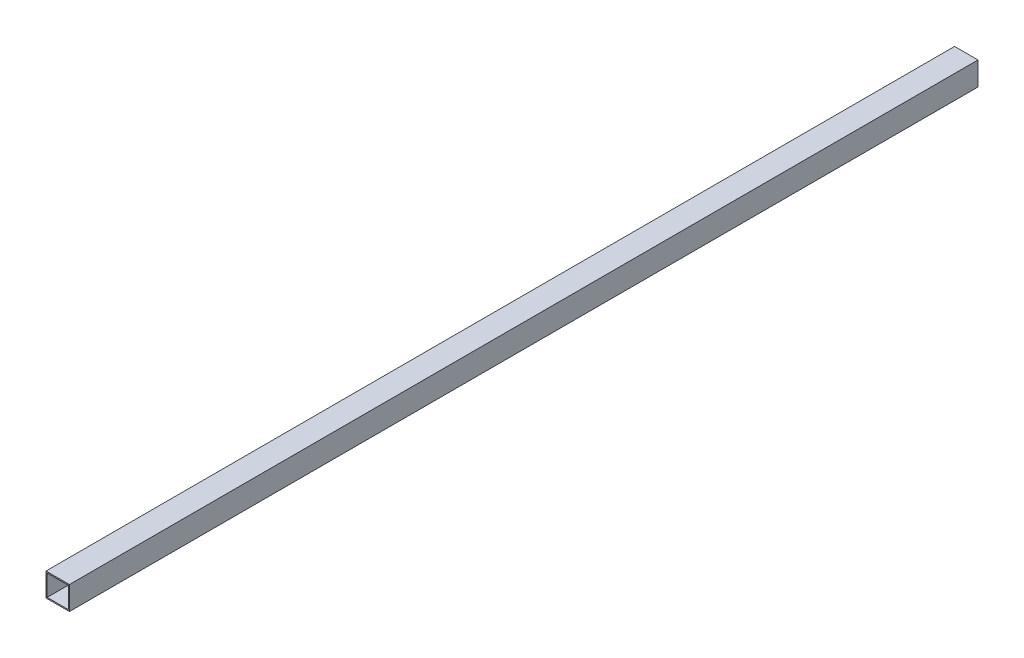
SolidWorks part; units mm, degrees
ref_plane "Front Plane" through (0, 0, 0) normal (0, 0, 1) x (1, 0, 0)
ref_plane "Top Plane" through (0, 0, 0) normal (0, 1, 0) x (1, 0, 0)
ref_plane "Right Plane" through (0, 0, 0) normal (1, 0, 0) x (0, 0, -1)
sketch "Sketch1" plane through (0, 0, 0) normal (0, 0, 1) x (1, 0, 0)
  line L0 (-590, 825) -> (40, 825) construction
  line L1 (-590, 1650) -> (-590, 0) construction
  line L2 (40, 1650) -> (40, 0) construction
  line L3 (-550, 1650) -> (-550, 0) construction
  line L4 (-590, 845) -> (-550, 845)
  line L5 (-590, 845) -> (-590, 805)
  line L6 (-590, 805) -> (-550, 805)
  line L7 (-550, 845) -> (-550, 805)
  line L8 (-588, 843) -> (-552, 843)
  line L9 (-552, 843) -> (-552, 807)
  line L10 (-588, 807) -> (-552, 807)
  line L11 (-588, 843) -> (-588, 807)
  dimension "D1" = 40
  dimension "D2" = 20
  dimension "D3" = 2
extrude "Boss-Extrude1" add sketch "Sketch1" along normal up to surface (1551.5 mm away)
